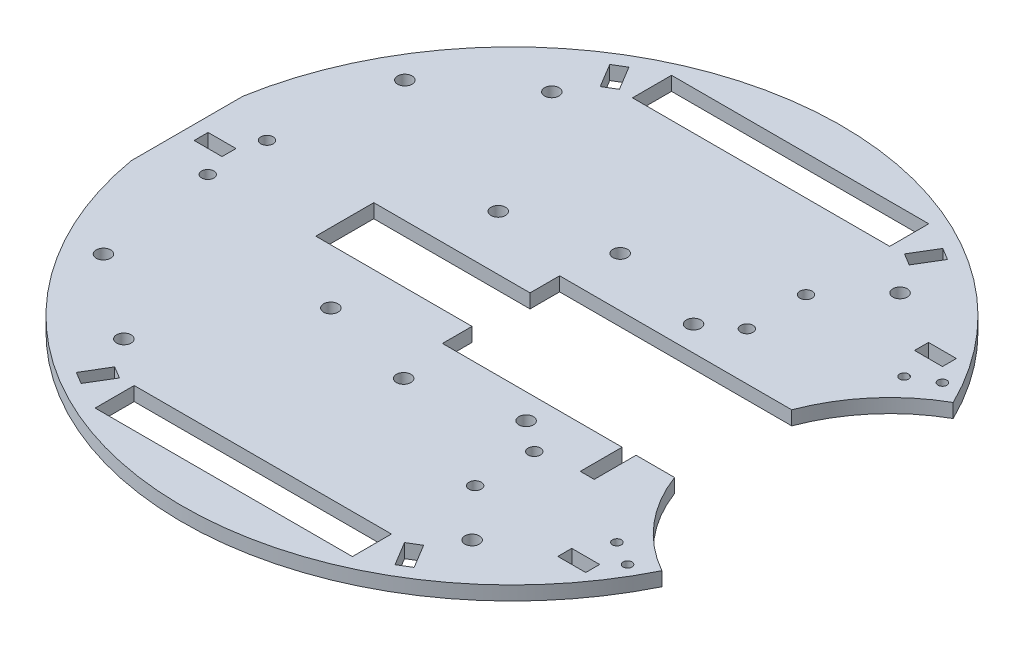
SolidWorks part; units mm, degrees
material "Acrylic (Medium-high impact)"
ref_plane "Front Plane" through (0, 0, 0) normal (0, 0, 1) x (1, 0, 0)
ref_plane "Top Plane" through (0, 0, 0) normal (0, 1, 0) x (1, 0, 0)
ref_plane "Right Plane" through (0, 0, 0) normal (1, 0, 0) x (0, 0, -1)
sketch "Sketch1" plane through (0, 0, 0) normal (0, 1, 0) x (1, 0, 0)
  line L0 (67.2709, 33.1606) -> (86.0323, 0) construction
  line L1 (86.0323, 0) -> (67.2709, -33.1606) construction
  line L2 (0, 65.5895) -> (0, 75) construction
  line L3 (-29.2721, -56.6995) -> (29.2721, -56.6995)
  line L4 (-29.2721, -56.6995) -> (-29.2721, -65.5895)
  line L5 (-29.2721, -65.5895) -> (29.2721, -65.5895)
  line L6 (29.2721, -56.6995) -> (29.2721, -65.5895)
  line L7 (-29.2721, 65.5895) -> (29.2721, 65.5895)
  line L8 (-29.2721, 65.5895) -> (-29.2721, 56.6995)
  line L9 (-29.2721, 56.6995) -> (29.2721, 56.6995)
  line L10 (29.2721, 65.5895) -> (29.2721, 56.6995)
  line L11 (29.2721, 65.5895) -> (30.566, 68.4888) construction
  line L12 (29.2721, -65.5895) -> (30.566, -68.4888) construction
  line L13 (-62.4869, 6.731) -> (-62.4869, -6.731) construction
  line L14 (-62.4869, 0) -> (-73.9169, 0) construction
  line L16 (58.9661, -42.1806) -> (52.6161, -42.1806)
  line L17 (58.9661, -42.1806) -> (58.9661, -39.0056)
  line L18 (58.9661, -39.0056) -> (52.6161, -39.0056)
  line L19 (52.6161, -42.1806) -> (52.6161, -39.0056)
  line L20 (58.9661, 42.1806) -> (52.6161, 42.1806)
  line L21 (58.9661, 42.1806) -> (58.9661, 39.0056)
  line L22 (60.7114, 44.0354) -> (67.2709, 33.1606) construction
  line L23 (0, 0) -> (86.0323, 0) construction
  line L24 (52.6161, 42.1806) -> (52.6161, 39.0056)
  line L25 (58.9661, 39.0056) -> (52.6161, 39.0056)
  line L28 (-39.6269, -48.6985) -> (0, -24.638) construction
  line L29 (0, -24.638) -> (39.6269, -48.6985) construction
  line L30 (-39.6269, -48.6985) -> (39.6269, -48.6985) construction
  line L31 (0, -24.638) -> (0, -48.6985) construction
  line L32 (-2.4867, 6.604) -> (-2.4867, 13.335) construction
  line L33 (38.4073, -13.335) -> (-2.4867, -13.335) construction
  line L34 (-2.4867, -13.335) -> (-2.4867, -6.604) construction
  line L35 (-2.4867, 13.335) -> (38.4073, 13.335) construction
  line L36 (38.4073, 13.335) -> (41.5823, 13.335)
  line L37 (32.441, -56.8953) -> (35.7191, -62.3337)
  line L38 (32.441, -56.8953) -> (35.1602, -55.2563)
  line L39 (35.7191, -62.3337) -> (38.4383, -60.6947)
  line L40 (35.1602, -55.2563) -> (38.4383, -60.6947)
  line L41 (-58.6769, -34.29) -> (-58.6769, 34.29) construction
  line L42 (0, 0) -> (-16.51, 0) construction
  line L43 (-58.6769, 0) -> (-62.4869, 0) construction
  line L44 (41.5823, 13.335) -> (50.3421, 13.335)
  line L45 (41.5823, -13.335) -> (46.2813, -13.335)
  line L46 (-2.4867, -6.604) -> (-2.4867, -13.335)
  line L47 (-73.9169, 12.7) -> (-73.9169, -12.7)
  line L48 (38.4073, 13.335) -> (-2.4867, 13.335)
  line L49 (-2.4867, 13.335) -> (-2.4867, 6.604)
  line L50 (-2.4867, -13.335) -> (38.4073, -13.335)
  line L51 (46.2813, -13.335) -> (50.3421, -13.335)
  line L52 (-2.4867, 0) -> (-38.0467, 0) construction
  line L53 (-2.4867, 6.604) -> (-38.0467, 6.604)
  line L54 (14.856, 13.335) -> (14.856, 0) construction
  line L55 (-2.4867, -6.604) -> (-38.0467, -6.604)
  line L56 (-38.0467, 6.604) -> (-38.0467, -6.604)
  line L57 (14.856, 0) -> (14.856, -13.335) construction
  line L58 (32.441, -56.8953) -> (38.4383, -60.6947) construction
  line L59 (35.7191, -62.3337) -> (35.1602, -55.2563) construction
  line L60 (41.5823, -13.335) -> (41.5823, -22.86)
  line L61 (41.5823, -22.86) -> (38.4073, -22.86)
  line L62 (38.4073, -13.335) -> (38.4073, -22.86)
  line L63 (33.8006, -56.0758) -> (0, 0) construction
  line L64 (37.0787, -61.5142) -> (38.7178, -64.2334) construction
  line L65 (-32.441, -56.8953) -> (-35.1602, -55.2563)
  line L66 (-32.441, -56.8953) -> (-35.7191, -62.3337)
  line L67 (-35.7191, -62.3337) -> (-38.4383, -60.6947)
  line L68 (-35.1602, -55.2563) -> (-38.4383, -60.6947)
  line L69 (-35.1602, 55.2563) -> (-38.4383, 60.6947)
  line L70 (-32.441, 56.8953) -> (-35.1602, 55.2563)
  line L71 (-32.441, 56.8953) -> (-35.7191, 62.3337)
  line L72 (-35.7191, 62.3337) -> (-38.4383, 60.6947)
  line L73 (35.1602, 55.2563) -> (38.4383, 60.6947)
  line L74 (32.441, 56.8953) -> (35.1602, 55.2563)
  line L75 (32.441, 56.8953) -> (35.7191, 62.3337)
  line L76 (35.7191, 62.3337) -> (38.4383, 60.6947)
  line L77 (-73.9169, 0) -> (-70.7419, 0) construction
  line L78 (-70.7419, 1.5875) -> (-64.3919, 1.5875)
  line L79 (-70.7419, 1.5875) -> (-70.7419, -1.5875)
  line L80 (-70.7419, -1.5875) -> (-64.3919, -1.5875)
  line L81 (-64.3919, 1.5875) -> (-64.3919, -1.5875)
  arc A0 (67.2709, 33.1606) -> (-73.9169, 12.7) centre (0, 0) ccw
  arc A1 (67.2709, -33.1606) -> (55.0862, -22.225) centre (86.0323, 0) cw
  circle A2 centre (-62.4869, 6.731) radius 1.397
  circle A3 centre (-62.4869, -6.731) radius 1.397
  circle A4 centre (-39.6269, -48.6985) radius 1.651
  circle A5 centre (39.6269, -48.6985) radius 1.651
  circle A6 centre (39.6269, 48.6985) radius 1.651
  circle A7 centre (0, -24.638) radius 1.651
  circle A8 centre (-39.6269, 48.6985) radius 1.651
  circle A9 centre (0, 24.638) radius 1.651
  circle A10 centre (29.2721, -37.6495) radius 1.397
  arc A11 (55.0862, -22.225) -> (50.3421, -13.335) centre (86.0323, 0) cw
  circle A12 centre (-58.6769, 34.29) radius 1.651
  circle A13 centre (62.1411, -35.8306) radius 1.016
  circle A14 centre (56.5708, -32.6791) radius 1.016
  circle A15 centre (-58.6769, -34.29) radius 1.651
  arc A16 (50.3421, 13.335) -> (67.2709, 33.1606) centre (86.0323, 0) cw
  arc A17 (-73.9169, -12.7) -> (67.2709, -33.1606) centre (0, 0) ccw
  circle A18 centre (29.2721, -24.1875) radius 1.397
  circle A19 centre (29.2721, 37.6495) radius 1.397
  circle A20 centre (29.2721, 24.1875) radius 1.397
  circle A25 centre (62.1411, 35.8306) radius 1.016
  circle A26 centre (56.5708, 32.6791) radius 1.016
  circle A27 centre (56.5708, 32.6791) radius 1.016 construction
  circle A28 centre (22.2783, 19.05) radius 1.651
  circle A29 centre (22.2783, -19.05) radius 1.651
  circle A30 centre (-22.1717, -19.05) radius 1.651
  circle A31 centre (-22.1717, 19.05) radius 1.651
  circle A32 centre (22.2783, 19.05) radius 1.651 construction
  point P50 (41.5823, 0)
  point P56 (47.9323, 0)
  point P63 (35.4397, -58.795)
  dimension "D1" = 150
  dimension "D7" = 11.43
  dimension "D8" = 2.794
  dimension "D14" = 24.0605
  dimension "D16" = 3.302
  dimension "D22" = 13.208
  dimension "D27" = 3.302
  dimension "D34" = 2.794
  dimension "D2" = 121
  dimension "D3" = 38.1
  dimension "D4" = 58.5441
  dimension "D5" = 8.89
  dimension "D6" = 3.175
  dimension "D9" = 13.462
  dimension "D10" = 6.35
  dimension "D11" = 3.175
  dimension "D12" = 3.175
  dimension "D13" = 3.175
  dimension "D15" = 3.175
  dimension "D18" = 25.4
  dimension "D19" = 26.67
  dimension "D20" = 44.069
  dimension "D21" = 17.3428
  dimension "D23" = 38.1
  dimension "D24" = 9.525
  dimension "D25" = 15.24
  dimension "D26" = 68.58
  dimension "D28" = 44.45
  dimension "D29" = 35.56
  dimension "D30" = 6.35
  dimension "D31" = 88.519
  dimension "D32" = 16.51
  dimension "D33" = 13.462
  dimension "D35" = 19.05
  dimension "D37" = 3.175
  dimension "D38" = 3.175
  dimension "D39" = 3.175
extrude "Boss-Extrude1" add sketch "Sketch1" along normal blind 3.175
equation "\"Diameter\"= 2.75"
equation "\"D4@Sketch1\"=\"Diameter\"*sin(arccos(1-(5/(4*\"Diameter\"))))"
